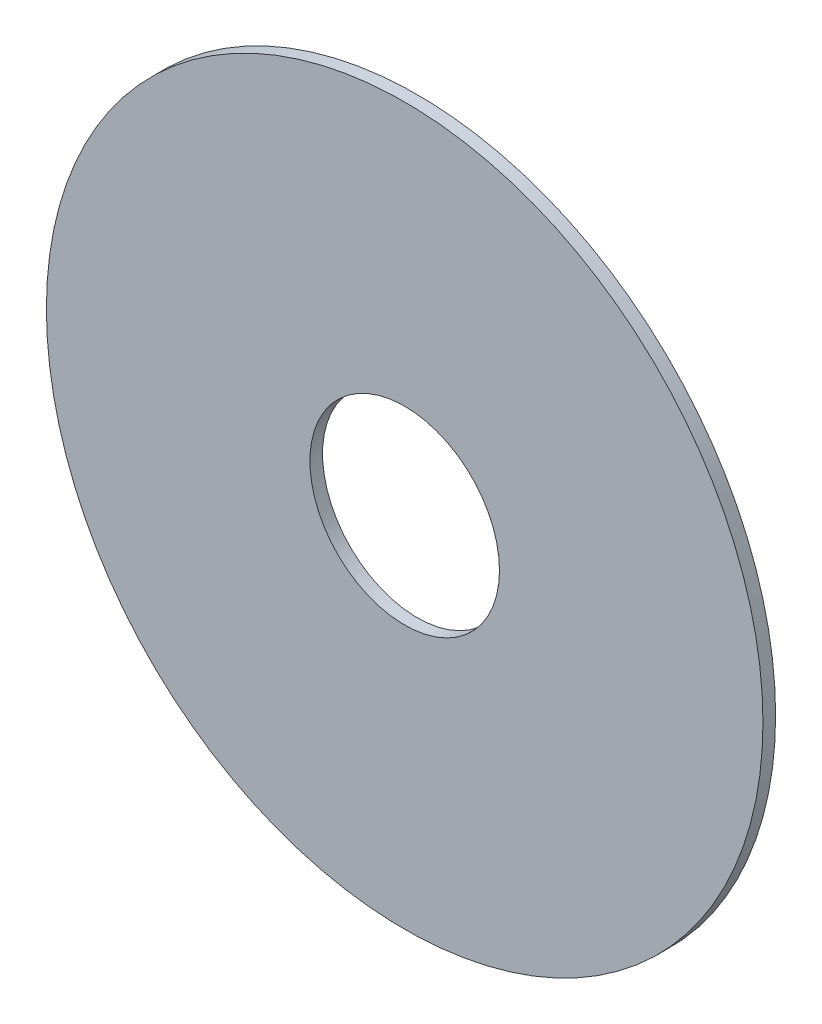
SolidWorks part; units mm, degrees
ref_plane "Front Plane" through (0, 0, 0) normal (0, 0, 1) x (1, 0, 0)
ref_plane "Top Plane" through (0, 0, 0) normal (0, 1, 0) x (1, 0, 0)
ref_plane "Right Plane" through (0, 0, 0) normal (1, 0, 0) x (0, 0, -1)
sketch "Sketch1" plane through (0, 0, 0) normal (0, 0, 1) x (1, 0, 0)
  circle A0 centre (0, 0) radius 28.35
  circle A1 centre (0, 0) radius 7.5
  dimension "D1" = 56.7
  dimension "D2" = 15
extrude "Boss-Extrude1" add sketch "Sketch1" along normal blind 1
sketch "Sketch2" plane through (0, 0, 1) normal (0, 0, 1) x (1, 0, 0)
  line L0 (-28.35, 0) -> (28.35, 0) construction
  circle A0 centre (0, 0) radius 28.35 construction
  circle A1 centre (0, 0) radius 23.35
  dimension "D1" = 5
